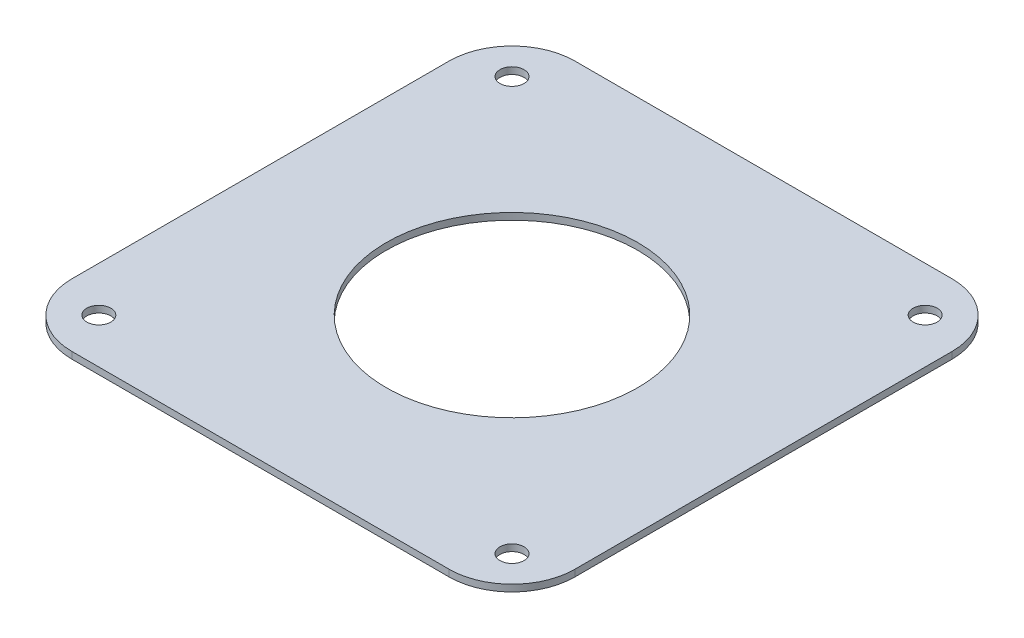
SolidWorks part; units mm, degrees
material "Stainless Steel (ferritic)"
ref_plane "Front Plane" through (0, 0, 0) normal (0, 0, 1) x (1, 0, 0)
ref_plane "Top Plane" through (0, 0, 0) normal (0, 1, 0) x (1, 0, 0)
ref_plane "Right Plane" through (0, 0, 0) normal (1, 0, 0) x (0, 0, -1)
sketch "Sketch1" plane through (0, 0, 0) normal (0, 1, 0) x (1, 0, 0)
  line L1 (-35.56, 35.56) -> (35.56, 35.56)
  line L2 (-35.56, 35.56) -> (-35.56, -35.56)
  line L3 (-35.56, -35.56) -> (35.56, -35.56)
  line L4 (35.56, 35.56) -> (35.56, -35.56)
  line L5 (-35.56, 35.56) -> (35.56, -35.56) construction
  line L6 (-35.56, -35.56) -> (35.56, 35.56) construction
  line L7 (-29.21, 29.21) -> (29.21, 29.21) construction
  line L8 (-29.21, 29.21) -> (-29.21, -29.21) construction
  line L9 (-29.21, -29.21) -> (29.21, -29.21) construction
  line L10 (29.21, 29.21) -> (29.21, -29.21) construction
  line L11 (-29.21, 29.21) -> (29.21, -29.21) construction
  line L12 (-29.21, -29.21) -> (29.21, 29.21) construction
  circle A0 centre (0, 0) radius 17.78
  circle A1 centre (-29.21, 29.21) radius 2.032 construction
  circle A2 centre (-29.21, -29.21) radius 2.032 construction
  circle A3 centre (29.21, -29.21) radius 2.032 construction
  circle A4 centre (29.21, 29.21) radius 2.032 construction
  point P0 (0, 0)
  dimension "D3" = 35.56
  dimension "D5" = 4.064
  dimension "D1" = 71.12
  dimension "D2" = 71.12
  dimension "D4" = 58.42
extrude "Boss-Extrude1" add sketch "Sketch1" along normal blind 0.9525
fillet "Fillet1" radius 8.89 4 edges at (35.56, 0.4762, -35.56) (-35.56, 0.4762, -35.56) (-35.56, 0.4762, 35.56) (35.56, 0.4762, 35.56)
hole_wizard "M3 Clearance Hole1" positions "Sketch2" profile "Sketch3" hole size "M3" standard "ANSI Metric" end condition through all
sketch "Sketch2" plane through (0, 0.9525, 0) normal (0, 1, 0) x (1, 0, 0)
  point P0 (-29.21, -29.21)
  point P3 (29.21, -29.21)
  point P6 (29.21, 29.21)
  point P9 (-29.21, 29.21)
sketch "Sketch3" plane through (-29.21, 0.9525, 29.21) normal (1, 0, 0) x (0, 0, 1)
  line L0 (0, 0) -> (0, 0.9525)
  line L1 (0, 0.9525) -> (1.7, 0.9525)
  line L2 (1.7, 0.9525) -> (1.7, 0)
  line L5 (1.7, 0) -> (0, 0)
  line L11 (0, -6.35) -> (0, 107.95) construction
  dimension "Thru Hole Dia." = 3.4
  dimension "Thru Hole Depth" = 0.9525
